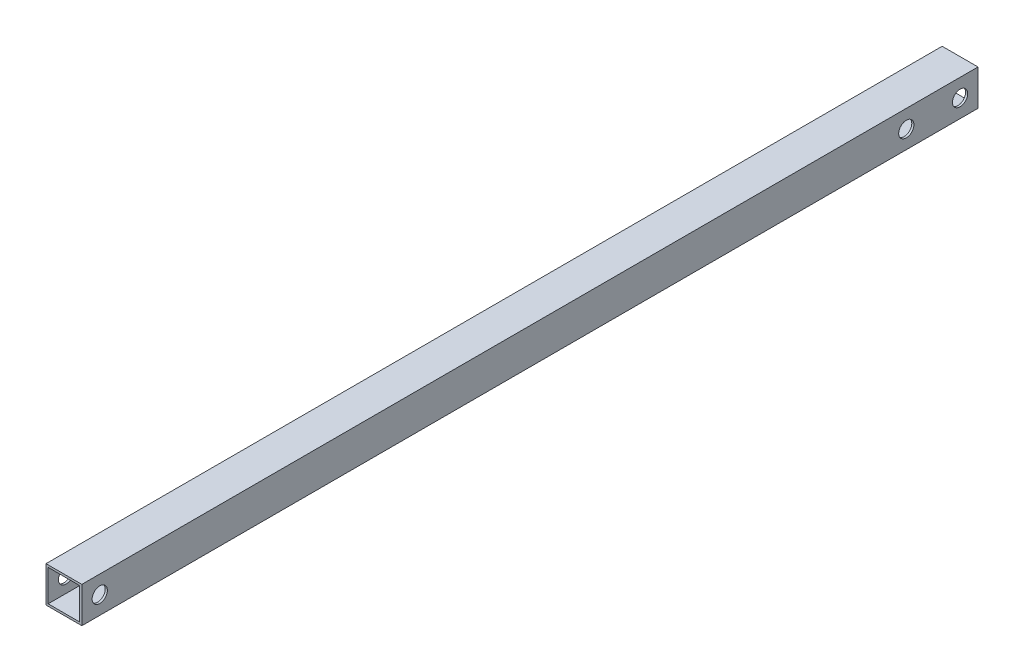
SolidWorks part; units mm, degrees
ref_plane "Front Plane" through (0, 0, 0) normal (0, 0, 1) x (1, 0, 0)
ref_plane "Top Plane" through (0, 0, 0) normal (0, 1, 0) x (1, 0, 0)
ref_plane "Right Plane" through (0, 0, 0) normal (1, 0, 0) x (0, 0, -1)
sketch "Sketch1" plane through (0, 0, 0) normal (0, 0, 1) x (1, 0, 0)
  line L0 (-8.8, 8.8) -> (-8.8, -8.8)
  line L1 (-10, 10) -> (10, 10)
  line L2 (-10, 10) -> (-10, -10)
  line L3 (-10, -10) -> (10, -10)
  line L4 (10, 10) -> (10, -10)
  line L5 (-10, 10) -> (10, -10) construction
  line L6 (-10, -10) -> (10, 10) construction
  line L7 (-8.8, -8.8) -> (8.8, -8.8)
  line L8 (8.8, 8.8) -> (8.8, -8.8)
  line L9 (-8.8, 8.8) -> (8.8, 8.8)
  point P0 (0, 0)
  dimension "D1" = 20
  dimension "D2" = 1.2
extrude "Boss-Extrude1" add sketch "Sketch1" along normal blind 500
sketch "Sketch2" plane through (10, 0, 0) normal (1, 0, 0) x (0, 0, -1)
  line L0 (-500, 0) -> (-490, 0) construction
  line L1 (-500, -10) -> (-500, 10) construction
  line L2 (0, 0) -> (-10, 0) construction
  line L3 (0, -10) -> (0, 10) construction
  line L4 (-10, 0) -> (-40, 0) construction
  circle A0 centre (-490, 0) radius 4.25
  circle A1 centre (-10, 0) radius 4.25
  circle A2 centre (-40, 0) radius 4.25
  point P6 (0, 0)
  point P14 (0, 0)
  dimension "D2" = 8.5
  dimension "D3" = 10
  dimension "D1" = 10
  dimension "D4" = 30
extrude "Cut-Extrude1" cut sketch "Sketch2" against normal blind 600
